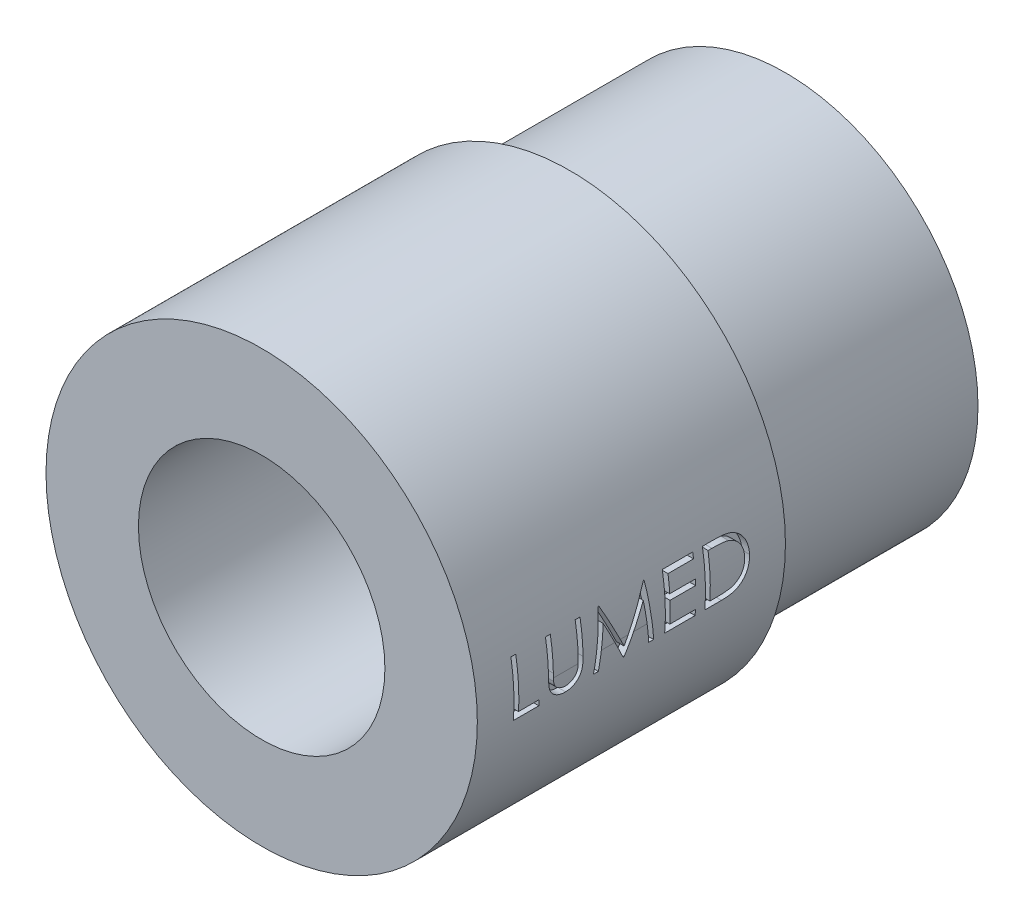
SolidWorks part; units mm, degrees
material "Plain Carbon Steel"
ref_plane "Front Plane" through (0, 0, 0) normal (0, 0, 1) x (1, 0, 0)
ref_plane "Top Plane" through (0, 0, 0) normal (0, 1, 0) x (1, 0, 0)
ref_plane "Right Plane" through (0, 0, 0) normal (1, 0, 0) x (0, 0, -1)
sketch "Sketch1" plane through (0, 0, 0) normal (0, 0, 1) x (1, 0, 0)
  circle A0 centre (0, 0) radius 12.5
  dimension "D1" = 25
extrude "SmallO.D." add sketch "Sketch1" along normal blind 14
sketch "Sketch2" plane through (0, 0, 14) normal (0, 0, 1) x (1, 0, 0)
  circle A0 centre (0, 0) radius 14
  dimension "D1" = 28
extrude "LargeO.D." add sketch "Sketch2" along normal blind 20
sketch "Sketch3" plane through (0, 0, 34) normal (0, 0, 1) x (1, 0, 0)
  circle A0 centre (0, 0) radius 8
  dimension "D1" = 16
extrude "Bore" cut sketch "Sketch3" against normal through all
sketch "Sketch4" plane through (0, 0, 0) normal (1, 0, 0) x (0, 0, -1)
  line L0 (-32.0702, -1.137) -> (-16.1521, -1.137) construction
  text T0 "LUMED"
extrude "Cut-Extrude2" cut sketch "Sketch4" against normal offset from surface (6.548 mm away) 0.5 from offset 20
